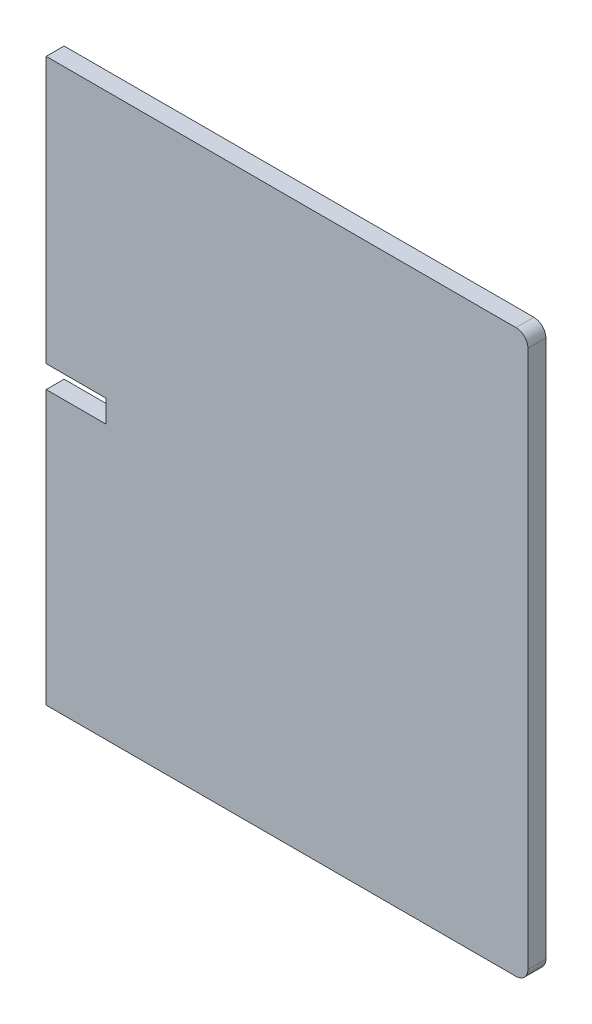
SolidWorks part; units mm, degrees
material "Polyurethane Foam Flexible"
ref_plane "Front Plane" through (0, 0, 0) normal (0, 0, 1) x (1, 0, 0)
ref_plane "Top Plane" through (0, 0, 0) normal (0, 1, 0) x (1, 0, 0)
ref_plane "Right Plane" through (0, 0, 0) normal (1, 0, 0) x (0, 0, -1)
sketch "Sketch1" plane through (0, 0, 0) normal (0, 0, 1) x (1, 0, 0)
  line L1 (39.9171, -20.7979) -> (66.385, -20.7979)
  line L3 (2.1352, -140.1779) -> (66.385, -140.1779)
  line L4 (68.925, -23.3379) -> (68.925, -137.6379)
  line L14 (68.925, -20.7979) -> (68.925, -80.4879)
  line L15 (39.9171, -20.7979) -> (-33.437, -20.7979)
  line L16 (-33.437, -20.7979) -> (-33.437, -140.1779)
  line L17 (-33.437, -140.1779) -> (2.1352, -140.1779)
  line L18 (-20.737, -82.1072) -> (-20.737, -77.3447)
  line L19 (-33.437, -80.4879) -> (-33.437, -68.9222)
  line L22 (-20.737, -82.1072) -> (-33.437, -82.1072)
  line L23 (-33.437, -82.1072) -> (-33.437, -80.4879)
  line L24 (-20.737, -77.3447) -> (-33.437, -77.3447)
  arc A2 (68.925, -23.3379) -> (66.385, -20.7979) centre (66.385, -23.3379) ccw
  arc A3 (68.925, -137.6379) -> (66.385, -140.1779) centre (66.385, -137.6379) cw
  point P4 (-20.737, -79.7259)
  point P19 (68.925, -20.7979)
  point P22 (68.925, -140.1779)
  dimension "D1" = 102.362
  dimension "D3" = 4.7625
  dimension "D4" = 2.54
  dimension "D2" = 119.38
  dimension "D5" = 59.69
  dimension "D6" = 60.452
  dimension "D7" = 12.7
  dimension "D8" = 13.185
extrude "Boss-Extrude1" add sketch "Sketch1" along normal blind 3.81
